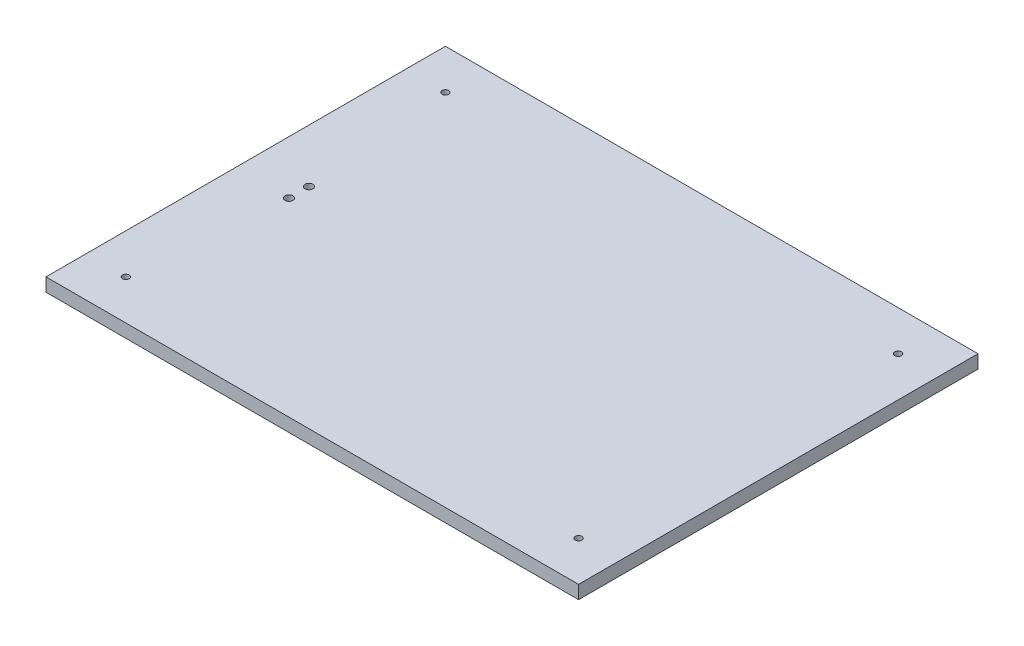
SolidWorks part; units mm, degrees
material "1060 Alloy"
ref_plane "Front Plane" through (0, 0, 0) normal (0, 0, 1) x (1, 0, 0)
ref_plane "Top Plane" through (0, 0, 0) normal (0, 1, 0) x (1, 0, 0)
ref_plane "Right Plane" through (0, 0, 0) normal (1, 0, 0) x (0, 0, -1)
sketch "BasePlate" plane through (0, 0, 0) normal (0, 1, 0) x (1, 0, 0)
  line L0 (-200, 0) -> (200, 0) construction
  line L1 (-200, 150) -> (200, 150)
  line L2 (-200, 150) -> (-200, -150)
  line L3 (-200, -150) -> (200, -150)
  line L4 (200, 150) -> (200, -150)
  circle A0 centre (-160, 7.5) radius 3
  circle A1 centre (-160, -7.5) radius 3
  circle A2 centre (-170, 120) radius 2.5
  circle A3 centre (170, 120) radius 2.5
  circle A4 centre (170, -120) radius 2.5
  circle A5 centre (-170, -120) radius 2.5
  point P11 (-200, 0)
  dimension "D3" = 6
  dimension "D4" = 6
  dimension "D8" = 30
  dimension "D16" = 5
  dimension "D17" = 5
  dimension "D18" = 5
  dimension "D19" = 5
  dimension "D1" = 400
  dimension "D2" = 300
  dimension "D5" = 15
  dimension "D6" = 7.5
  dimension "D7" = 40
  dimension "D9" = 30
  dimension "D10" = 30
  dimension "D11" = 30
  dimension "D12" = 30
  dimension "D13" = 30
  dimension "D14" = 30
  dimension "D15" = 30
extrude "Boss-Extrude1" add sketch "BasePlate" along normal blind 10
